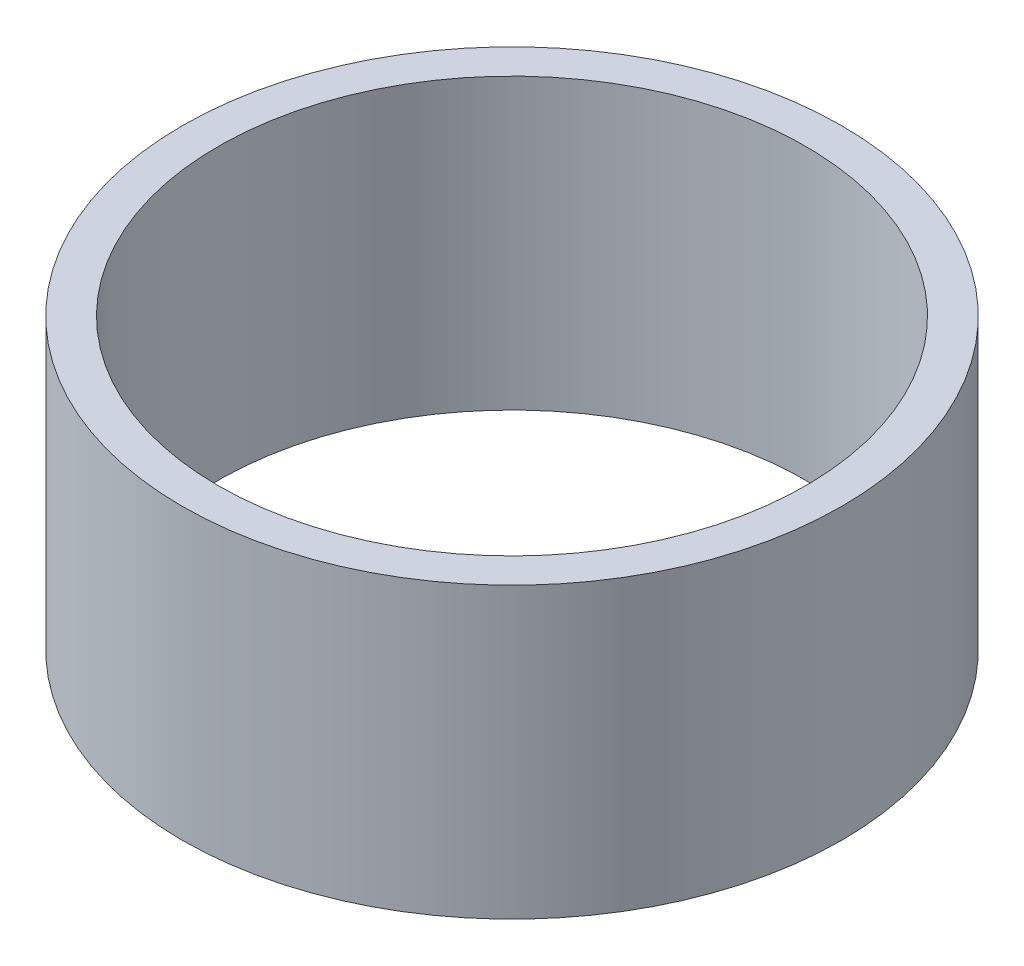
SolidWorks part; units mm, degrees
material "6061-T6 (SS)"
ref_plane "Front Plane" through (0, 0, 0) normal (0, 0, 1) x (1, 0, 0)
ref_plane "Top Plane" through (0, 0, 0) normal (0, 1, 0) x (1, 0, 0)
ref_plane "Right Plane" through (0, 0, 0) normal (1, 0, 0) x (0, 0, -1)
sketch "Sketch1" plane through (0, 0, 0) normal (0, 1, 0) x (1, 0, 0)
  circle A0 centre (0, 0) radius 14.25
  circle A1 centre (0, 0) radius 12.7
  dimension "D1" = 28.5
  dimension "D2" = 25.4
extrude "Boss-Extrude1" add sketch "Sketch1" along normal blind 12.5
